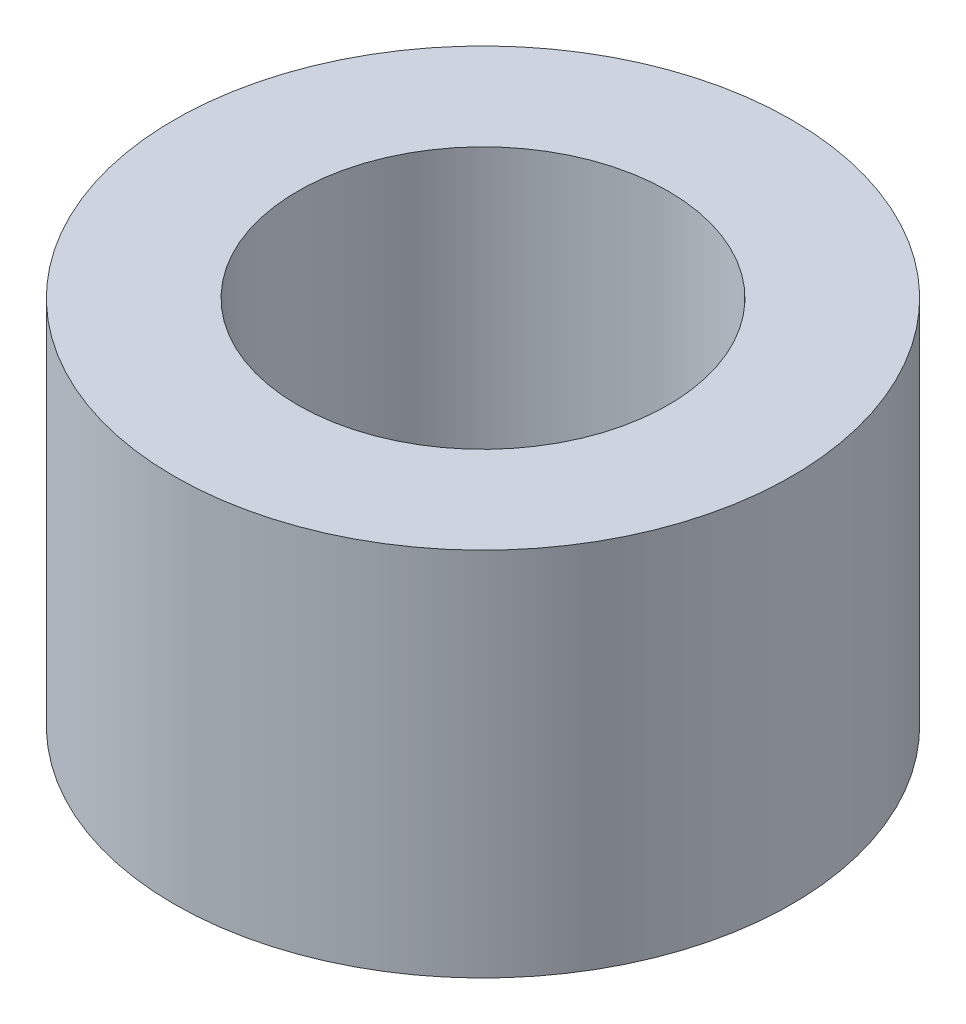
SolidWorks part; units mm, degrees
ref_plane "Спереди" through (0, 0, 0) normal (0, 0, 1) x (1, 0, 0)
ref_plane "Сверху" through (0, 0, 0) normal (0, 1, 0) x (1, 0, 0)
ref_plane "Справа" through (0, 0, 0) normal (1, 0, 0) x (0, 0, -1)
sketch "Эскиз1" plane through (0, 0, 0) normal (0, 1, 0) x (1, 0, 0)
  circle A0 centre (0, 0) radius 1.5
  circle A1 centre (0, 0) radius 2.5
extrude "Бобышка-Вытянуть1" add sketch "Эскиз1" along normal blind 3
